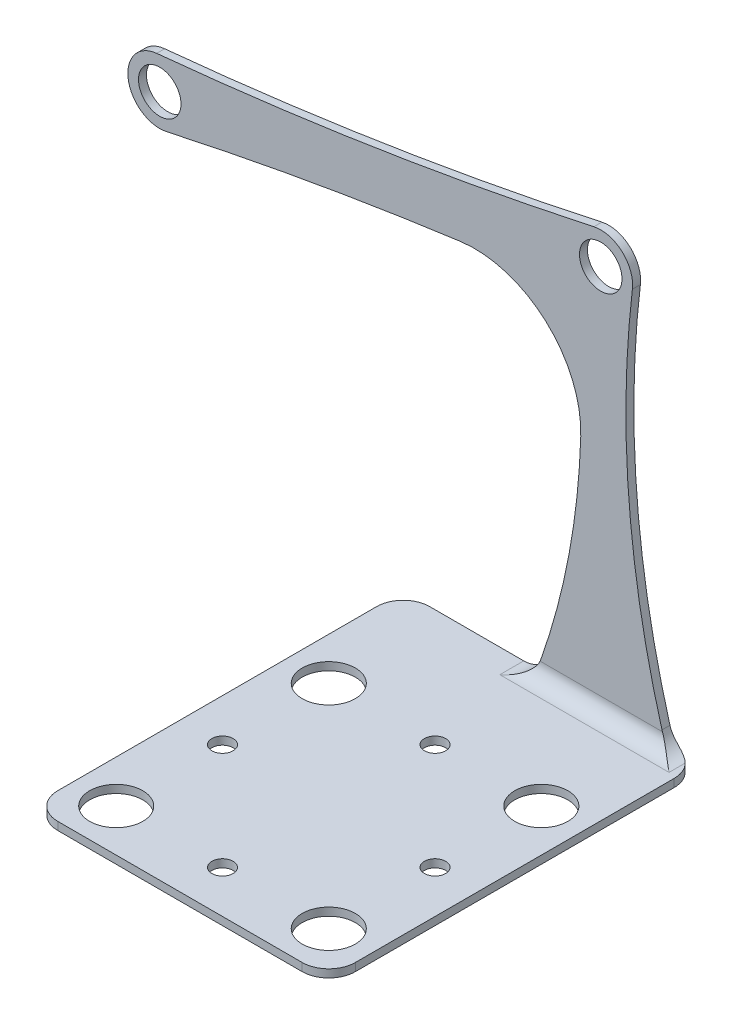
SolidWorks part; units mm, degrees
ref_plane "Front Plane" through (0, 0, 0) normal (0, 0, 1) x (1, 0, 0)
ref_plane "Top Plane" through (0, 0, 0) normal (0, 1, 0) x (1, 0, 0)
ref_plane "Right Plane" through (0, 0, 0) normal (1, 0, 0) x (0, 0, -1)
sketch "Sketch1" plane through (0, 0, 0) normal (0, 0, 1) x (1, 0, 0)
  line L0 (-91.063, -14.2601) -> (82.9886, 12.9957) construction
  line L1 (0, 0) -> (0, 49.2499) construction
  line L2 (82.9886, 12.9957) -> (82.9886, -60.0043) construction
  line L3 (70.4886, -60.0043) -> (95.4886, -60.0043)
  circle A0 centre (0, 0) radius 4
  circle A1 centre (82.9886, 12.9957) radius 4
  arc A2 (-0.574, 5.9725) -> (1.2793, -5.862) centre (0, 0) ccw
  arc A3 (88.947, 12.29) -> (81.7094, 18.8577) centre (82.9886, 12.9957) ccw
  arc A4 (-0.574, 5.9725) -> (81.7094, 18.8577) centre (-67.5378, 702.7622) ccw
  arc A5 (1.2793, -5.862) -> (56.5587, 3.8977) centre (150.5264, -689.7665) cw
  arc A6 (88.947, 12.29) -> (95.4886, -60.0043) centre (263.3832, -8.3691) ccw
  circle A7 centre (82.9886, 12.9957) radius 6 construction
  arc A8 (82.9886, 6.9678) -> (83.5626, 7.0232) centre (150.5264, -689.7665) cw
  arc A9 (56.5587, 3.8977) -> (79.2333, -16.559) centre (59.2434, -15.9212) cw
  arc A10 (79.2333, -16.559) -> (70.4886, -60.0043) centre (-54.2157, -12.3012) cw
  dimension "D2" = 8
  dimension "D3" = 8
  dimension "D4" = 12
  dimension "D5" = 12
  dimension "D6" = 700
  dimension "D7" = 700
  dimension "D11" = 20
  dimension "D1" = 84
  dimension "D8" = 98.9
  dimension "D9" = 73
  dimension "D10" = 25
extrude "Boss-Extrude2" add sketch "Sketch1" along normal blind 1.5
sketch "Sketch2" plane through (0, -60.0043, 0) normal (0, -1, 0) x (1, 0, 0)
  line L0 (72.3086, -14.4772) -> (72.3086, 66.0315) construction
  line L1 (100.3086, 0) -> (44.3086, 0)
  line L2 (100.3086, 0) -> (100.3086, 70)
  line L3 (100.3086, 70) -> (44.3086, 70)
  line L4 (44.3086, 0) -> (44.3086, 70)
  line L6 (82.9886, -5.7784) -> (82.9886, 9.1254) construction
  line L7 (95.4886, 1.5) -> (95.4886, 0) construction
  line L8 (70.4886, 1.5) -> (70.4886, 0) construction
  line L9 (126.3484, 42) -> (-6.9516, 42) construction
  line L10 (70.4886, 0) -> (95.4886, 0) construction
  line L11 (92.3086, -9.8609) -> (92.3086, 108.4215) construction
  line L12 (52.3086, -12.4856) -> (52.3086, 95.7803) construction
  line L13 (122.1402, 22) -> (26.8381, 22) construction
  line L14 (113.7395, 62) -> (30.0438, 62) construction
  circle A0 centre (92.3086, 42) radius 2
  circle A1 centre (72.3086, 22) radius 2
  circle A2 centre (52.3086, 42) radius 2
  circle A3 centre (72.3086, 62) radius 2
  circle A4 centre (52.3086, 22) radius 5
  circle A5 centre (92.3086, 22) radius 5
  circle A6 centre (92.3086, 62) radius 5
  circle A7 centre (52.3086, 62) radius 5
  dimension "D5" = 4
  dimension "D6" = 10
  dimension "D1" = 10.68
  dimension "D2" = 42
  dimension "D3" = 40
  dimension "D4" = 40
  dimension "D7" = 28
  dimension "D8" = 28
extrude "Boss-Extrude3" add sketch "Sketch2" along normal blind 1.5
fillet "Fillet1" radius 5 4 edges at (100.3086, -60.7543, 70) (44.3086, -60.7543, 70) (44.3086, -60.7543, 0) (100.3086, -60.7543, 0)
fillet "Fillet3" radius 5 1 edges at (70.4886, -60.0043, 0.75)
fillet "Fillet4" radius 4.5 1 edges at (95.4886, -60.0043, 0.7516)
fillet "Fillet5" radius 3 1 edges at (82.9227, -60.0043, 1.5)
